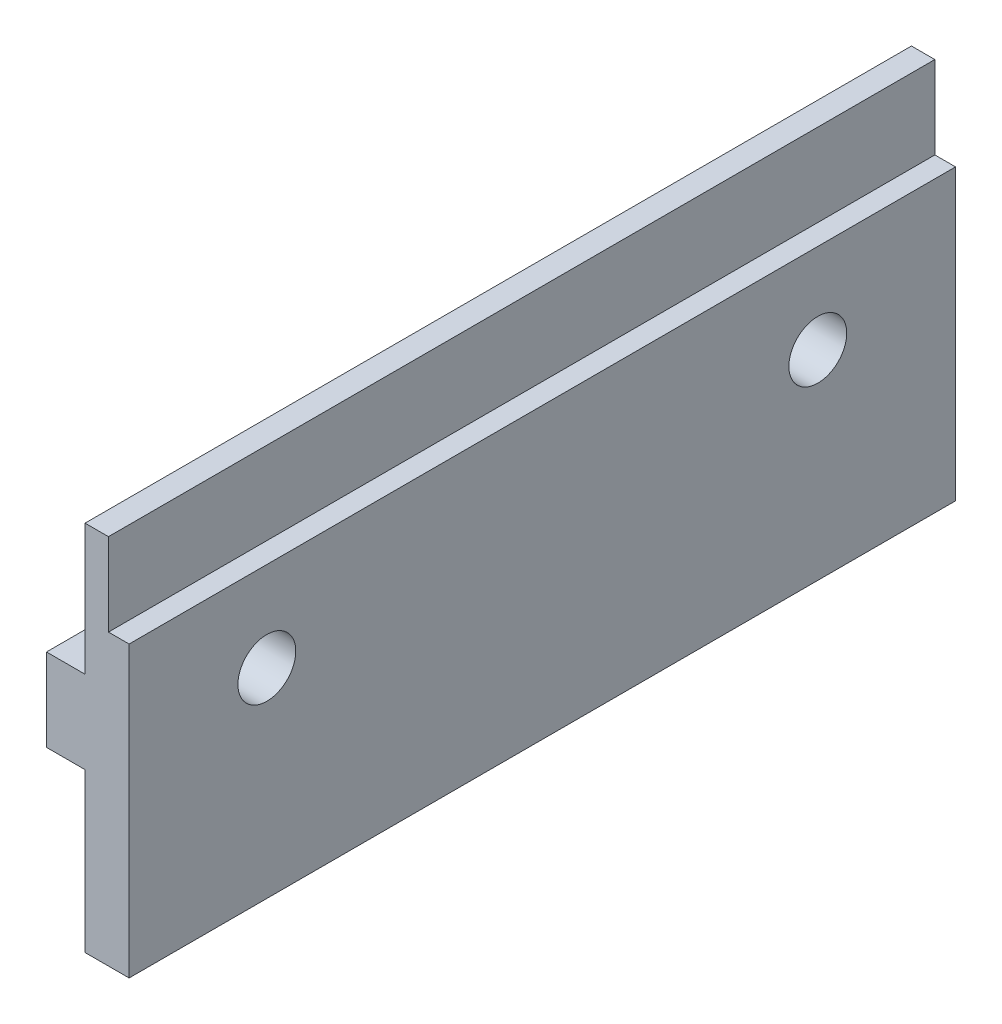
SolidWorks part; units mm, degrees
ref_plane "Front Plane" through (0, 0, 0) normal (0, 0, 1) x (1, 0, 0)
ref_plane "Top Plane" through (0, 0, 0) normal (0, 1, 0) x (1, 0, 0)
ref_plane "Right Plane" through (0, 0, 0) normal (1, 0, 0) x (0, 0, -1)
sketch "Sketch1" plane through (0, 0, 0) normal (1, 0, 0) x (0, 0, -1)
  line L1 (0, 0) -> (60, 0)
  line L2 (0, 0) -> (0, 27)
  line L3 (0, 27) -> (60, 27)
  line L4 (60, 0) -> (60, 27)
  dimension "D1" = 60
  dimension "D2" = 27
extrude "Boss-Extrude1" add sketch "Sketch1" along normal blind 6
sketch3d "3DSketch1"
  line L0 (6, 27, 0) -> (6, 0, 0) construction
  line L1 (6, 27, 0) -> (4.5, 27, 0)
  line L2 (6, 27, 0) -> (6, 21, 0)
  line L3 (6, 21, 0) -> (4.5, 21, 0)
  line L4 (4.5, 27, 0) -> (4.5, 21, 0)
  point P5 (0, 0, 0)
  dimension "D1" = 6
  dimension "D2" = 1.5
extrude "Cut-Extrude19" cut sketch "3DSketch1" along direction (0, 0, 1) on the side against the normal through all both and the other way through all
sketch "Sketch9" plane through (0, 0, -60) normal (0, 0, -1) x (-1, 0, 0)
  line L1 (0, 0) -> (-2.8, 0)
  line L2 (0, 0) -> (0, 11.5)
  line L3 (0, 11.5) -> (-2.8, 11.5)
  line L4 (-2.8, 0) -> (-2.8, 11.5)
  dimension "D1" = 11.5
  dimension "D2" = 2.8
extrude "Cut-Extrude20" cut sketch "Sketch9" against normal through all
sketch "Sketch10" plane through (0, 0, -60) normal (0, 0, -1) x (-1, 0, 0)
  line L1 (0, 27) -> (-2.8, 27)
  line L2 (0, 27) -> (0, 17.5)
  line L3 (0, 17.5) -> (-2.8, 17.5)
  line L4 (-2.8, 27) -> (-2.8, 17.5)
  dimension "D1" = 2.8
  dimension "D2" = 9.5
extrude "Cut-Extrude21" cut sketch "Sketch10" against normal through all both and the other way through all
sketch "Sketch11" plane through (0, 0, 0) normal (-1, 0, 0) x (0, 0, 1)
  line L0 (-60, 14.5) -> (0, 14.5) construction
  line L1 (-60, 11.5) -> (-60, 17.5) construction
  line L2 (0, 17.5) -> (0, 11.5) construction
  line L3 (-50, 14.5) -> (-50, 15.1548) construction
  line L4 (-10, 14.5) -> (-10, 15.1548) construction
  point P10 (-50, 15.1548)
  point P11 (0, 0)
  point P12 (-50, 14.5)
  point P13 (0, 0)
  point P14 (0, 0)
  point P15 (-10, 14.5)
  dimension "D1" = 10
  dimension "D2" = 40
  dimension "D3" = 10
hole_wizard "M5 Tapped Hole3" positions "3DSketch11" profile "Sketch25" tap size "M5" standard "DIN"
sketch3d "3DSketch11"
  point P0 (0, 14.5, -50)
sketch "Sketch25" plane through (0, 14.5, -50) normal (0, 1, 0) x (0, 0, 1)
  line L0 (0, 0) -> (0, 13.6618)
  line L1 (0, 13.6618) -> (2.1, 12.4)
  line L2 (2.1, 12.4) -> (2.1, 0)
  line L5 (2.1, 0) -> (0, 0)
  line L10 (0, 13.6618) -> (-2.1, 12.4) construction
  line L11 (0, -6.35) -> (0, 107.95) construction
  dimension "Tap Drill Dia." = 4.2
  dimension "Tap Drill Depth" = 12.4
  dimension "Drill Angle" = 118
cosmetic thread "Hole Thread8" parameters "D1"=6, "D2"=5
hole_wizard "M5 Tapped Hole4" positions "3DSketch12" profile "Sketch26" tap size "M5" standard "DIN"
sketch3d "3DSketch12"
  point P0 (0, 14.5, -10)
sketch "Sketch26" plane through (0, 14.5, -10) normal (0, 1, 0) x (0, 0, 1)
  line L0 (0, 0) -> (0, 13.6618)
  line L1 (0, 13.6618) -> (2.1, 12.4)
  line L2 (2.1, 12.4) -> (2.1, 0)
  line L5 (2.1, 0) -> (0, 0)
  line L10 (0, 13.6618) -> (-2.1, 12.4) construction
  line L11 (0, -6.35) -> (0, 107.95) construction
  dimension "Tap Drill Dia." = 4.2
  dimension "Tap Drill Depth" = 12.4
  dimension "Drill Angle" = 118
cosmetic thread "Hole Thread9" parameters "D1"=6, "D2"=5
